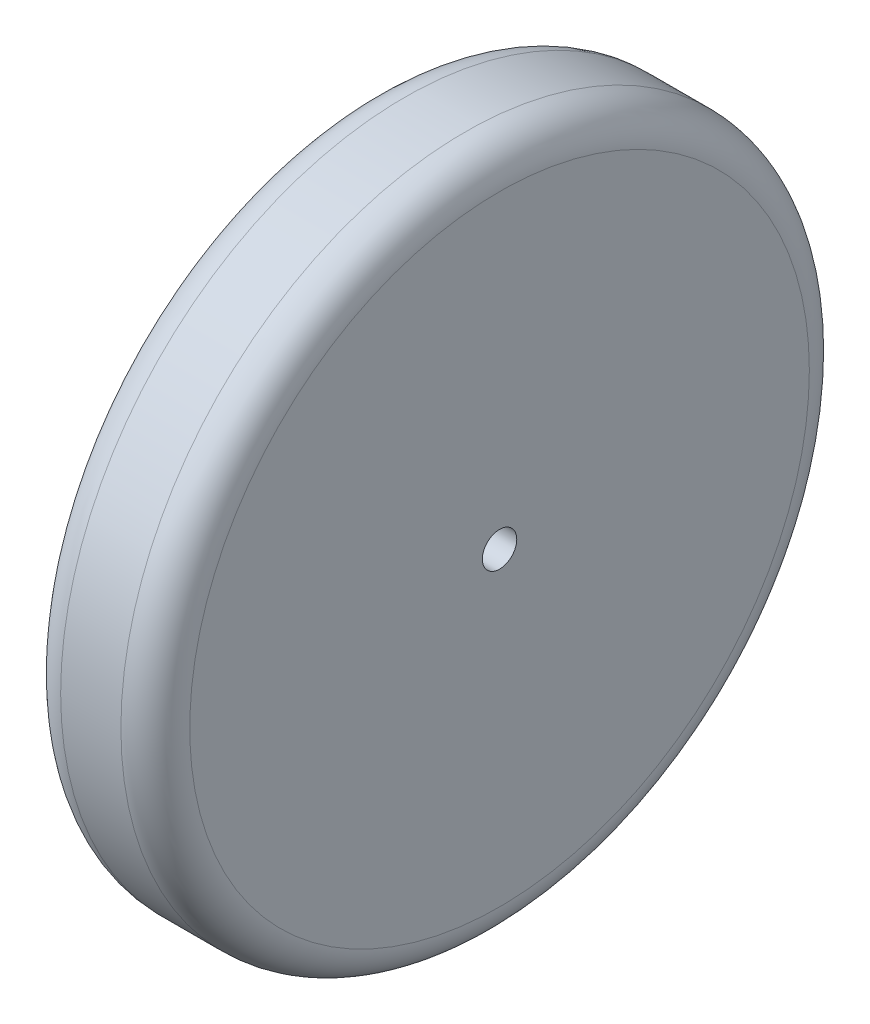
SolidWorks part; units mm, degrees
ref_plane "Front Plane" through (0, 0, 0) normal (0, 0, 1) x (1, 0, 0)
ref_plane "Top Plane" through (0, 0, 0) normal (0, 1, 0) x (1, 0, 0)
ref_plane "Right Plane" through (0, 0, 0) normal (1, 0, 0) x (0, 0, -1)
sketch "Sketch1" plane through (0, 0, 0) normal (1, 0, 0) x (0, 0, -1)
  circle A0 centre (0, 0) radius 200
  circle A1 centre (0, 0) radius 10
  dimension "D1" = 400
  dimension "D2" = 20
extrude "Boss-Extrude1" add sketch "Sketch1" along normal mid plane 75
fillet "Fillet1" radius 20 2 edges at (-37.5, 0, -200) (37.5, 0, -200)
